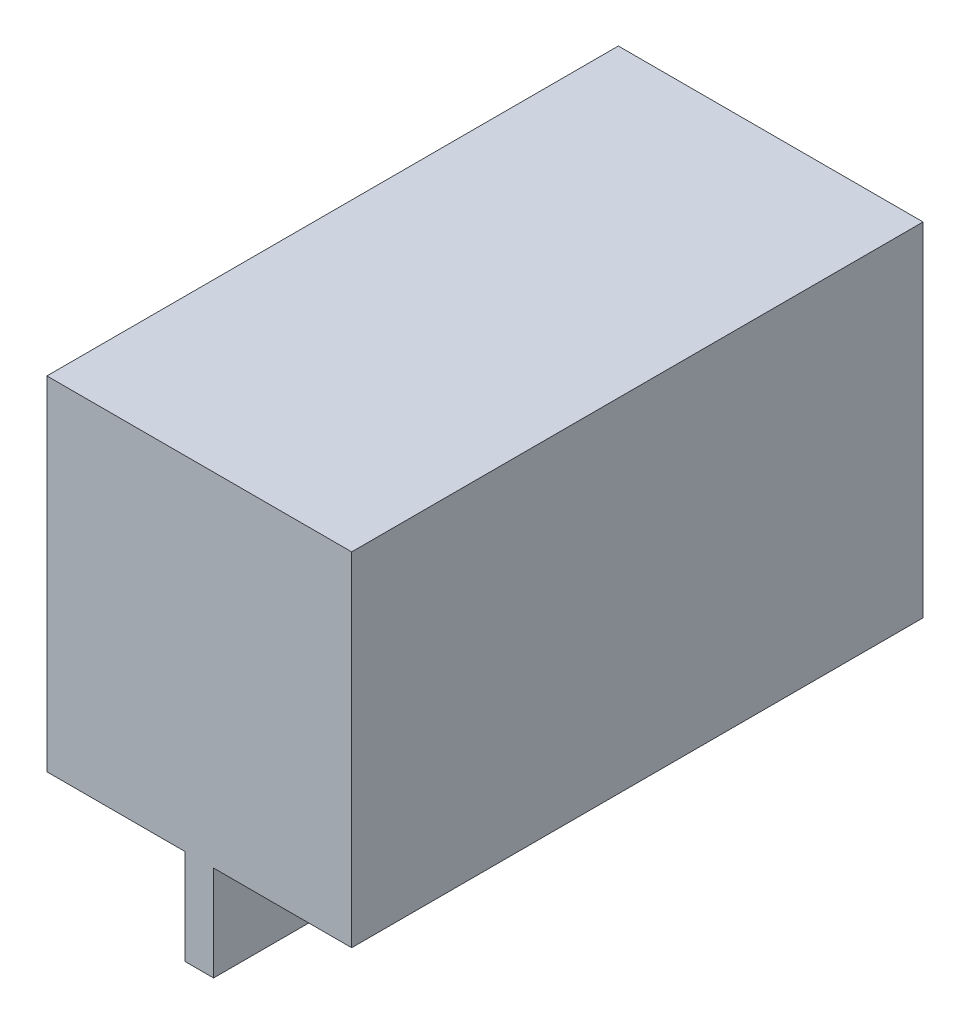
SolidWorks part; units mm, degrees
ref_plane "Front Plane" through (0, 0, 0) normal (0, 0, 1) x (1, 0, 0)
ref_plane "Top Plane" through (0, 0, 0) normal (0, 1, 0) x (1, 0, 0)
ref_plane "Right Plane" through (0, 0, 0) normal (1, 0, 0) x (0, 0, -1)
sketch "Эскиз1" plane through (0, 0, 0) normal (0, 1, 0) x (1, 0, 0)
  line L0 (0, 0) -> (16, 0)
  line L1 (16, 0) -> (16, 30)
  line L2 (0, 0) -> (0, 30)
  line L3 (0, 30) -> (16, 30)
extrude "Бобышка-Вытянуть1" add sketch "Эскиз1" along normal blind 18
sketch "Эскиз2" plane through (0, 0, 0) normal (0, -1, 0) x (1, 0, 0)
  line L0 (8, 0) -> (8, -30) construction
  line L1 (0, 0) -> (16, 0) construction
  line L2 (16, -30) -> (0, -30) construction
  line L3 (0, -15) -> (16, -15) construction
  line L4 (0, -30) -> (0, 0) construction
  line L5 (16, 0) -> (16, -30) construction
  line L6 (7.25, -15) -> (7.25, 0)
  line L7 (7.25, -15) -> (7.25, -30)
  line L8 (8.75, -15) -> (8.75, 0)
  line L9 (8.75, -15) -> (8.75, -30)
  line L10 (7.25, 0) -> (8.75, 0)
  line L11 (7.25, -30) -> (8.75, -30)
extrude "Бобышка-Вытянуть2" add sketch "Эскиз2" along normal blind 5
